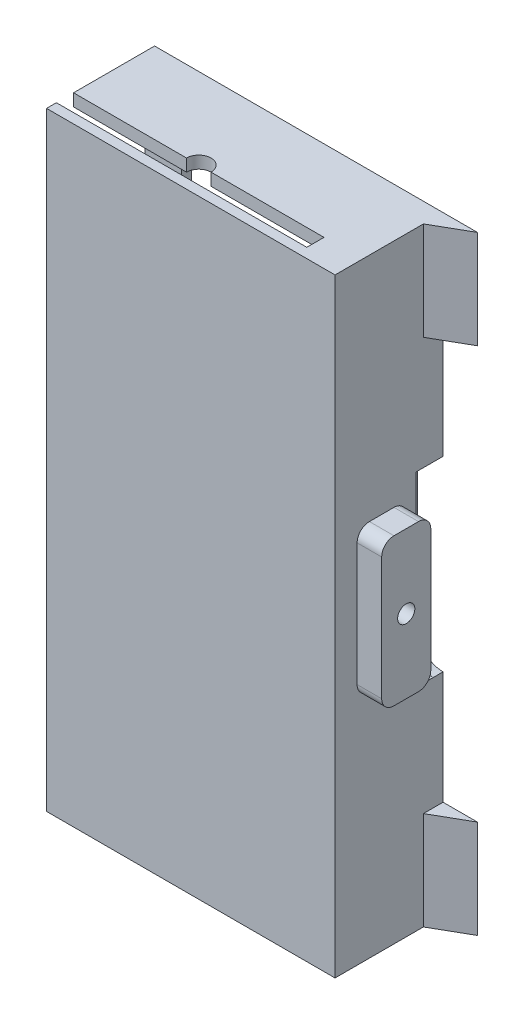
SolidWorks part; units mm, degrees
ref_plane "Front Plane" through (0, 0, 0) normal (1, 0, 0) x (0, 1, 0)
ref_plane "Top Plane" through (0, 0, 0) normal (0, 0, 1) x (0, 1, 0)
ref_plane "Right Plane" through (0, 0, 0) normal (0, 1, 0) x (-1, 0, 0)
sketch "Croquis1" plane through (0, 0, 0) normal (0, 0, 1) x (0, 1, 0)
  line L0 (0, -49.6) -> (0, 49.6) construction
  line L1 (-49.6, 0) -> (49.6, 0) construction
  line L2 (49.6, -36) -> (-49.6, -36) construction
  line L3 (49.6, -19.4) -> (-49.6, -19.4) construction
  line L5 (49.6, -23.4) -> (-49.6, -23.4) construction
  line L6 (-49.6, -19.4) -> (49.6, -19.4)
  line L7 (-49.6, -19.4) -> (-49.6, 27.6)
  line L8 (-49.6, 27.6) -> (49.6, 27.6)
  line L9 (49.6, -19.4) -> (49.6, 27.6)
  line L10 (49.6, -22.4) -> (-49.6, -22.4) construction
  point P4 (0, 0)
  point P8 (0, 0)
  point P11 (0, -36)
  point P13 (0, -19.4)
  point P16 (0, -19.5201)
  point P21 (0, -23.4)
  point P23 (0, -22.4)
  dimension "D1" = 99.2
  dimension "D2" = 99.2
  dimension "D3" = 13.6
  dimension "D4" = 22
  dimension "D5" = 16.6
  dimension "D6" = 13.6
  dimension "D7" = 12.6
extrude "BASE" add sketch "Croquis1" along normal blind 17.6
sketch "Croquis2" plane through (-27.6, 0, 0) normal (-1, 0, 0) x (0, -1, 0)
  line L0 (0, 0) -> (0, 1.6) construction
  line L1 (-47.6, 16) -> (-17.2, 16)
  line L2 (-47.6, 16) -> (-47.6, 1.6)
  line L3 (-47.6, 1.6) -> (-17.2, 1.6)
  line L4 (-17.2, 16) -> (-17.2, 1.6)
  line L5 (-15.2, 16) -> (15.2, 16)
  line L6 (-15.2, 16) -> (-15.2, 1.6)
  line L7 (-15.2, 1.6) -> (15.2, 1.6)
  line L8 (15.2, 16) -> (15.2, 1.6)
  line L9 (17.2, 16) -> (47.6, 16)
  line L10 (17.2, 16) -> (17.2, 1.6)
  line L11 (17.2, 1.6) -> (47.6, 1.6)
  line L12 (47.6, 16) -> (47.6, 1.6)
  line L13 (-49.6, 0) -> (49.6, 0) construction
  line L14 (-15.2, 8.8) -> (-17.2, 8.8) construction
  line L15 (15.2, 8.8) -> (17.2, 8.8) construction
  line L16 (49.6, 8.8) -> (47.6, 8.8) construction
  line L18 (49.6, 17.6) -> (49.6, 0) construction
  line L19 (-49.6, 8.8) -> (-47.6, 8.8) construction
  line L20 (-49.6, 17.6) -> (-49.6, 0) construction
  line L21 (-49.6, 17.6) -> (49.6, 17.6) construction
  dimension "D1" = 1.6
  dimension "D2" = 1.6
  dimension "D3" = 30.4
extrude "PLATES" cut sketch "Croquis2" against normal blind 40.8
sketch "Croquis4" plane through (-27.6, 0, 0) normal (-1, 0, 0) x (0, -1, 0)
  line L0 (49.6, 17.6) -> (49.6, 0) construction
  line L1 (47.6, 16) -> (49.6, 16)
  line L2 (47.6, 16) -> (47.6, 13.2)
  line L3 (47.6, 13.2) -> (49.6, 13.2)
  line L4 (49.6, 16) -> (49.6, 13.2)
  line L5 (-49.6, 17.6) -> (-49.6, 0) construction
  line L6 (-47.6, 16) -> (-49.6, 16)
  line L7 (-47.6, 16) -> (-47.6, 13.2)
  line L8 (-47.6, 13.2) -> (-49.6, 13.2)
  line L9 (-49.6, 16) -> (-49.6, 13.2)
  dimension "D1" = 2.8
extrude "WINDOW_LATERAL_1" cut sketch "Croquis4" against normal up to surface (40.8 mm away) up to face at (13.2, -32.4, 8.8)
sketch "Croquis5" plane through (0, -49.6, 0) normal (0, -1, 0) x (1, 0, 0)
  line L0 (13.2, 13.2) -> (-27.6, 13.2) construction
  circle A0 centre (-7.2, 13.2) radius 2
  dimension "D1" = 4
extrude "WINDOW_LATERAL_2" cut sketch "Croquis5" against normal up to surface (2 mm away) up to face at (-7.2, -47.6, 7.4)
sketch "Croquis6" plane through (0, 49.6, 0) normal (0, 1, 0) x (-1, 0, 0)
  line L0 (9.2, 13.2) -> (5.2, 13.2)
  arc A0 (5.2, 13.2) -> (9.2, 13.2) centre (7.2, 13.2) ccw construction
  arc A1 (5.2, 13.2) -> (9.2, 13.2) centre (7.2, 13.2) ccw
extrude "WINDOW_LATERAL_3" cut sketch "Croquis6" against normal up to surface (2 mm away) up to face at (-7.2, 47.6, 7.4)
sketch "Croquis7" plane through (13.2, 0, 0) normal (-1, 0, 0) x (0, -1, 0)
  line L0 (-15.2, 16) -> (-15.2, 1.6) construction
  line L1 (15.2, 1.6) -> (-15.2, 1.6)
  line L2 (15.2, 1.6) -> (15.2, 4.4)
  line L3 (15.2, 4.4) -> (-15.2, 4.4)
  line L4 (-15.2, 1.6) -> (-15.2, 4.4)
  dimension "D1" = 2.8
extrude "WINDOW_BEHIND_1" cut sketch "Croquis7" against normal up to surface (6.2 mm away) up to face at (19.4, 0, 8.8)
sketch "Croquis8" plane through (0, 0, 1.6) normal (0, 0, 1) x (1, 0, 0)
  line L0 (19.4, -11) -> (19.4, 11) construction
  line L1 (19.4, -15.2) -> (19.4, 15.2) construction
  line L2 (15.2, -11) -> (15.2, 11)
  line L3 (23.6, -11) -> (23.6, 11)
  line L6 (13.2, -15.2) -> (13.2, 15.2) construction
  arc A0 (15.2, -11) -> (23.6, -11) centre (19.4, -11) ccw
  arc A1 (23.6, 11) -> (15.2, 11) centre (19.4, 11) ccw
  point P4 (19.4, 0)
  point P9 (19.4, 15.2)
  dimension "D1" = 2
extrude "WINDOW_BEHIND_2" cut sketch "Croquis8" against normal through all
sketch "Croquis9" plane through (0, 0, 1.6) normal (0, 0, 1) x (1, 0, 0)
  line L0 (15.2, 11) -> (15.2, -11) construction
  circle A0 centre (15.2, 0) radius 2
  dimension "D1" = 4
extrude "WINDOW_BEHIND_3" cut sketch "Croquis9" against normal through all
sketch "Croquis10" plane through (0, 0, 1.6) normal (0, 0, 1) x (1, 0, 0)
  line L0 (13.2, -17.2) -> (-27.6, -17.2) construction
  line L1 (-21.6, -32.4) -> (-27.6, -32.4) construction
  line L2 (-27.6, -17.2) -> (-27.6, -47.6) construction
  line L3 (-7.2, -43.6) -> (-7.2, -47.6) construction
  line L4 (13.2, -47.6) -> (-27.6, -47.6) construction
  line L5 (-27.6, -16.2) -> (15, -16.2) construction
  line L6 (-27.6, -15.2) -> (-27.6, -17.2) construction
  line L7 (-27.6, 17.2) -> (-27.6, 15.2) construction
  line L8 (-27.6, 16.2) -> (15, 16.2) construction
  line L9 (5.2, 11.2) -> (-19.6, 11.2)
  line L10 (-21.6, -9.2) -> (-21.6, 9.2)
  line L11 (5.2, -11.2) -> (-19.6, -11.2)
  line L12 (7.2, -9.2) -> (7.2, 9.2)
  line L13 (7.2, 41.6) -> (7.2, 23.2)
  line L14 (5.2, 43.6) -> (-19.6, 43.6)
  line L15 (-21.6, 41.6) -> (-21.6, 23.2)
  line L16 (5.2, 21.2) -> (-19.6, 21.2)
  line L32 (13.2, -17.2) -> (13.2, -47.6) construction
  line L33 (5.2, -21.2) -> (-19.6, -21.2)
  line L34 (7.2, -23.2) -> (7.2, -41.6)
  line L35 (5.2, -43.6) -> (-19.6, -43.6)
  line L36 (-21.6, -23.2) -> (-21.6, -41.6)
  arc A0 (5.2, -21.2) -> (7.2, -23.2) centre (5.2, -23.2) cw
  arc A1 (7.2, -41.6) -> (5.2, -43.6) centre (5.2, -41.6) cw
  arc A2 (-19.6, -43.6) -> (-21.6, -41.6) centre (-19.6, -41.6) cw
  arc A3 (-19.6, -21.2) -> (-21.6, -23.2) centre (-19.6, -23.2) ccw
  arc A4 (-19.6, 11.2) -> (-21.6, 9.2) centre (-19.6, 9.2) ccw
  arc A5 (-19.6, -11.2) -> (-21.6, -9.2) centre (-19.6, -9.2) cw
  arc A6 (5.2, -11.2) -> (7.2, -9.2) centre (5.2, -9.2) ccw
  arc A7 (7.2, 9.2) -> (5.2, 11.2) centre (5.2, 9.2) ccw
  arc A8 (7.2, 23.2) -> (5.2, 21.2) centre (5.2, 23.2) cw
  arc A9 (5.2, 43.6) -> (7.2, 41.6) centre (5.2, 41.6) cw
  arc A10 (-19.6, 43.6) -> (-21.6, 41.6) centre (-19.6, 41.6) ccw
  arc A11 (-19.6, 21.2) -> (-21.6, 23.2) centre (-19.6, 23.2) cw
  dimension "D1" = 2
  dimension "D2" = 6
  dimension "D3" = 4
extrude "WINDOW_BOTTOM" cut sketch "Croquis10" against normal through all
sketch "Croquis11" plane through (19.4, 0, 0) normal (1, 0, 0) x (0, 1, 0)
  line L0 (0, 0) -> (0, 6) construction
  line L1 (-10, 14) -> (10, 14)
  line L2 (-12, 12) -> (-12, 8)
  line L3 (-10, 6) -> (10, 6)
  line L4 (12, 12) -> (12, 8)
  line L6 (0, 6) -> (0, 14) construction
  line L7 (-49.6, 0) -> (-15.2, 0) construction
  arc A0 (10, 14) -> (12, 12) centre (10, 12) cw
  arc A1 (10, 6) -> (12, 8) centre (10, 8) ccw
  arc A2 (-12, 8) -> (-10, 6) centre (-10, 8) ccw
  arc A3 (-10, 14) -> (-12, 12) centre (-10, 12) ccw
  point P16 (0, 10)
  dimension "D1" = 2
  dimension "D2" = 10
  dimension "D3" = 24
  dimension "D4" = 8
extrude "ROTOR_JOIN_1" add sketch "Croquis11" along normal up to vertex (4 mm away) up to point (23.4, -49.6, 0)
sketch "Croquis12" plane through (23.4, 0, 0) normal (1, 0, 0) x (0, 1, 0)
  line L0 (0, 6) -> (0, 14) construction
  line L1 (-10, 6) -> (10, 6) construction
  line L2 (10, 14) -> (-10, 14) construction
  circle A0 centre (0, 10) radius 1.4
  dimension "D1" = 2.8
extrude "ROTOR_JOIN_2" cut sketch "Croquis12" against normal up to surface (10.2 mm away) up to face at (13.2, 0, 10.2)
sketch "Croquis14" plane through (0, -49.6, 0) normal (0, -1, 0) x (1, 0, 0)
  line L0 (19.4, 0) -> (19.4, 3.2)
  line L1 (19.4, 17.6) -> (19.4, 0) construction
  line L2 (19.4, 3.2) -> (25, 0)
  line L3 (25, 0) -> (19.4, 0)
  dimension "D1" = 3.2
  dimension "D2" = 5.6
extrude "ROTOR_LIMIT_1" add sketch "Croquis14" against normal blind 16
sketch "Croquis15" plane through (0, 49.6, 0) normal (0, 1, 0) x (-1, 0, 0)
  line L3 (-25, 0) -> (-19.4, 0)
  line L4 (-19.4, 0) -> (-19.4, 3.2)
  line L5 (-19.4, 3.2) -> (-25, 0)
  line L6 (-25, 0) -> (-19.4, 0)
  line L7 (-19.4, 0) -> (-19.4, 3.2)
  line L8 (-19.4, 3.2) -> (-25, 0)
  dimension "D1" = 0
extrude "ROTOR_LIMIT_2" add sketch "Croquis15" against normal blind 16
equation "\"jsumo_x\"= 18.4mm"
equation "\"jsumo_y\"= 14mm"
equation "\"jsumo_angle\"= 25deg"
equation "\"blade_join_z\"= 3.8mm"
